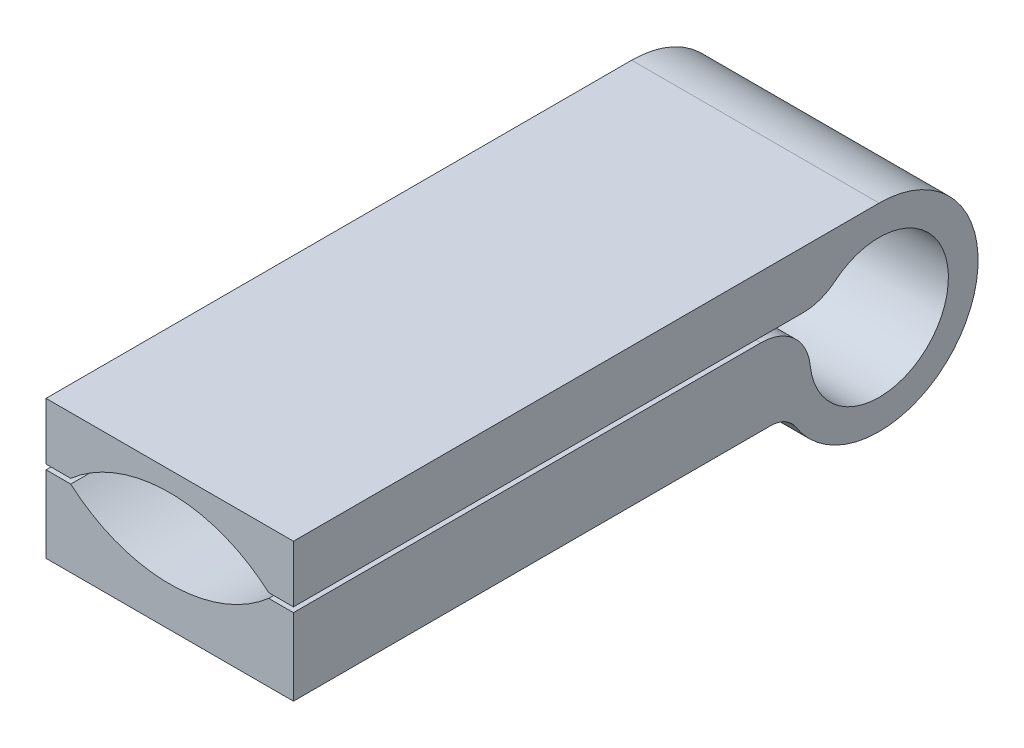
SolidWorks part; units mm, degrees
ref_plane "Front Plane" through (0, 0, 0) normal (0, 0, 1) x (1, 0, 0)
ref_plane "Top Plane" through (0, 0, 0) normal (0, 1, 0) x (1, 0, 0)
ref_plane "Right Plane" through (0, 0, 0) normal (1, 0, 0) x (0, 0, -1)
sketch "Sketch2" plane through (0, 0, 0) normal (1, 0, 0) x (0, 0, -1)
  line L0 (0, 0) -> (59.1652, 0)
  line L1 (0, 0) -> (0, -5.75)
  line L6 (45, -14) -> (0, -14)
  line L10 (47.2304, -6.25) -> (0, -6.25)
  line L11 (0, -14) -> (0, -6.25)
  line L14 (45, -14) -> (48.2107, -14)
  line L15 (0, -5.75) -> (51.5207, -5.75)
  arc A0 (54.7059, -4.6042) -> (52.2032, -10.7292) centre (59.1652, -10) cw
  arc A1 (59.1652, 0) -> (50.7387, -15.3846) centre (59.1652, -10) cw
  arc A2 (51.5207, -5.75) -> (54.7059, -4.6042) centre (51.5207, -0.75) ccw
  arc A3 (47.2304, -6.25) -> (52.2032, -10.7292) centre (47.2304, -11.25) cw
  arc A4 (48.2107, -14) -> (50.7387, -15.3846) centre (48.2107, -17) cw
  point P17 (0, -14)
  point P27 (50, -14)
  dimension "D1" = 3
  dimension "D7" = 10
  dimension "D9" = 5
  dimension "D4" = 5
  dimension "D8" = 5
  dimension "D10" = 3
  dimension "D2" = 7.75
  dimension "D3" = 0.5
  dimension "D5" = 45
  dimension "D6" = 5.75
extrude "Boss-Extrude2" add sketch "Sketch2" along normal blind 25
sketch "Sketch5" plane through (0, -14, 0) normal (0, -1, 0) x (1, 0, 0)
  line L6 (25, -48.2107) -> (0, -48.2107) construction
  circle A0 centre (12.5, -30.5607) radius 2.5
  circle A1 centre (12.5, -38.1907) radius 2.5
  circle A2 centre (12.5, -44.8407) radius 2.5
  point P6 (0, 0)
  point P8 (9.493, -29.7009)
  point P9 (0, 0)
  point P10 (0, 0)
  point P12 (0, 0)
  point P14 (0, -45)
  point P15 (0, -45)
  point P16 (0, -45)
  point P19 (0, 0)
  point P21 (12.5, -48.2107)
  point P22 (0.4941, -45)
  point P23 (0, 0)
  point P24 (0, 0)
  point P25 (0, 0)
  dimension "D1" = 5
  dimension "D2" = 5
  dimension "D3" = 5
  dimension "D4" = 3.37
  dimension "D5" = 10.02
  dimension "D6" = 17.65
extrude "Cut-Extrude1" cut sketch "Sketch5" against normal up to next
sketch "Sketch7" plane through (0, 0, 0) normal (0, 0, 1) x (1, 0, 0)
  line L0 (25, -5.75) -> (0, -5.75) construction
  line L1 (25, -6.25) -> (0, -6.25) construction
  line L4 (22.5, -6.25) -> (22.5, -5.75)
  line L5 (2.5, -5.75) -> (2.5, -6.25)
  arc A0 (2.5, -5.75) -> (22.5, -5.75) centre (12.5, -17.2083) cw
  arc A1 (2.5, -6.25) -> (22.5, -6.25) centre (12.5, 5.2083) ccw
  point P16 (12.5, -2)
  point P17 (12.5, -10)
  dimension "D1" = 20
  dimension "D2" = 8
  dimension "D3" = 2.5
extrude "Cut-Extrude4" cut sketch "Sketch7" against normal up to vertex (51.5207 mm away)
